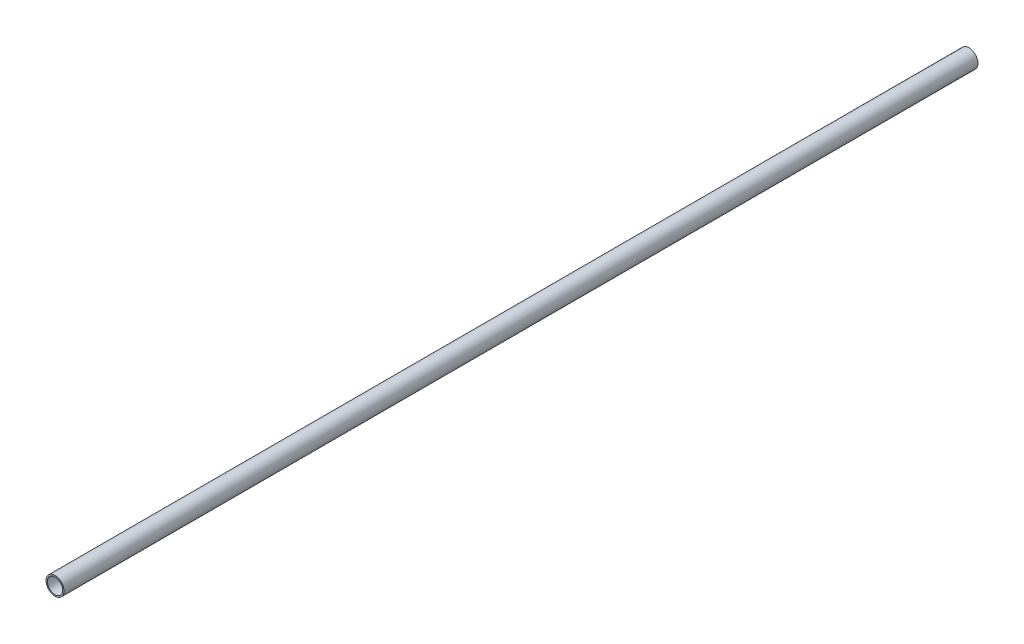
SolidWorks part; units mm, degrees
material "6063-T4"
ref_plane "Front Plane" through (0, 0, 0) normal (0, 0, 1) x (1, 0, 0)
ref_plane "Top Plane" through (0, 0, 0) normal (0, 1, 0) x (1, 0, 0)
ref_plane "Right Plane" through (0, 0, 0) normal (1, 0, 0) x (0, 0, -1)
sketch "Sketch1" plane through (0, 0, 0) normal (0, 0, 1) x (1, 0, 0)
  circle A0 centre (0, 0) radius 7.9
  circle A1 centre (0, 0) radius 6.7
  dimension "D1" = 15.8
  dimension "D2" = 1.2
extrude "Boss-Extrude1" add sketch "Sketch1" along normal blind 800
